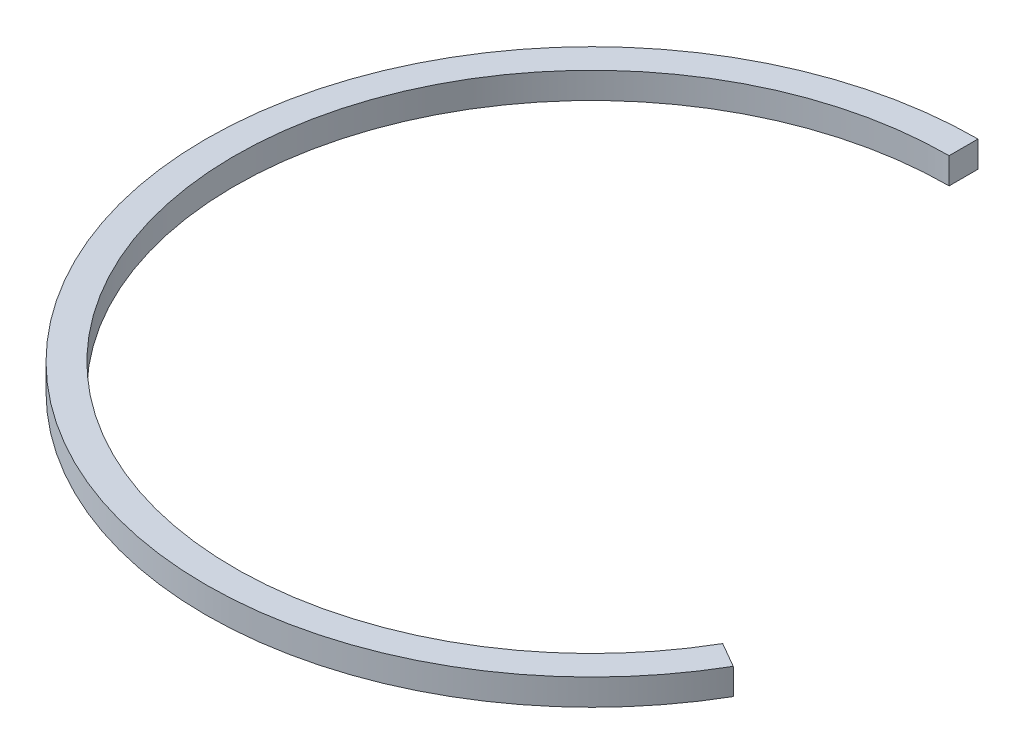
SolidWorks part; units mm, degrees
ref_plane "Front Plane" through (0, 0, 0) normal (0, 0, 1) x (1, 0, 0)
ref_plane "Top Plane" through (0, 0, 0) normal (0, 1, 0) x (1, 0, 0)
ref_plane "Right Plane" through (0, 0, 0) normal (1, 0, 0) x (0, 0, -1)
sketch "Sketch1" plane through (0, 0, 0) normal (0, 1, 0) x (1, 0, 0)
  line L0 (-39.8, 0) -> (0, 0) construction
  line L1 (-46.8, 0) -> (-39.8, 0) construction
  line L2 (0, 0) -> (22.5156, -41.0279) construction
  line L3 (0, 43.3) -> (0, 46.8)
  line L4 (37.4989, -21.65) -> (40.53, -23.4)
  line L5 (0, 43.3) -> (0, 46.8) construction
  line L6 (37.4989, -21.65) -> (0, 0) construction
  arc A0 (0, 46.8) -> (40.53, -23.4) centre (0, 0) ccw
  arc A4 (0, 43.3) -> (37.4989, -21.65) centre (0, 0) ccw
  point P6 (-46.8, 0)
  dimension "D1" = 93.6
  dimension "D2" = 3.5
  dimension "D4" = 120
  dimension "D3" = 7
extrude "Boss-Extrude1" add sketch "Sketch1" along normal blind 3.175
